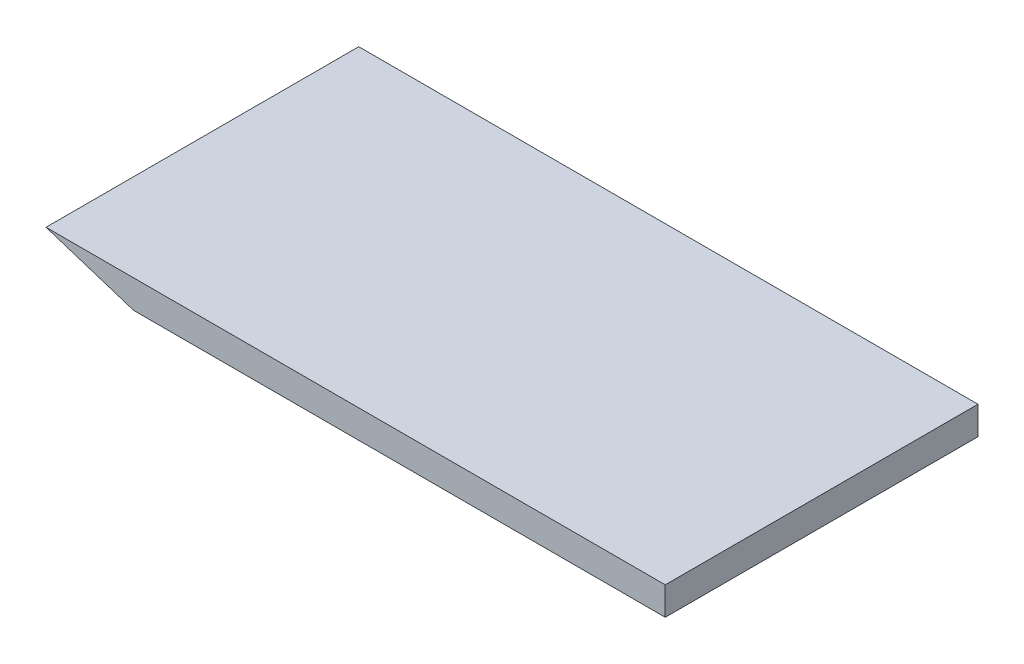
SolidWorks part; units mm, degrees
ref_plane "Front Plane" through (0, 0, 0) normal (0, 0, 1) x (1, 0, 0)
ref_plane "Top Plane" through (0, 0, 0) normal (0, 1, 0) x (1, 0, 0)
ref_plane "Right Plane" through (0, 0, 0) normal (1, 0, 0) x (0, 0, -1)
sketch "Sketch1" plane through (0, 0, 0) normal (0, 0, 1) x (1, 0, 0)
  line L0 (0, 0) -> (198, 0)
  line L1 (198, 0) -> (198, -9)
  line L2 (198, -9) -> (28, -9)
  line L3 (28, -9) -> (0, 0)
  dimension "D1" = 9
  dimension "D2" = 170
  dimension "D3" = 28
extrude "Boss-Extrude1" add sketch "Sketch1" along normal blind 100 contours L3 L0 L1 L2
